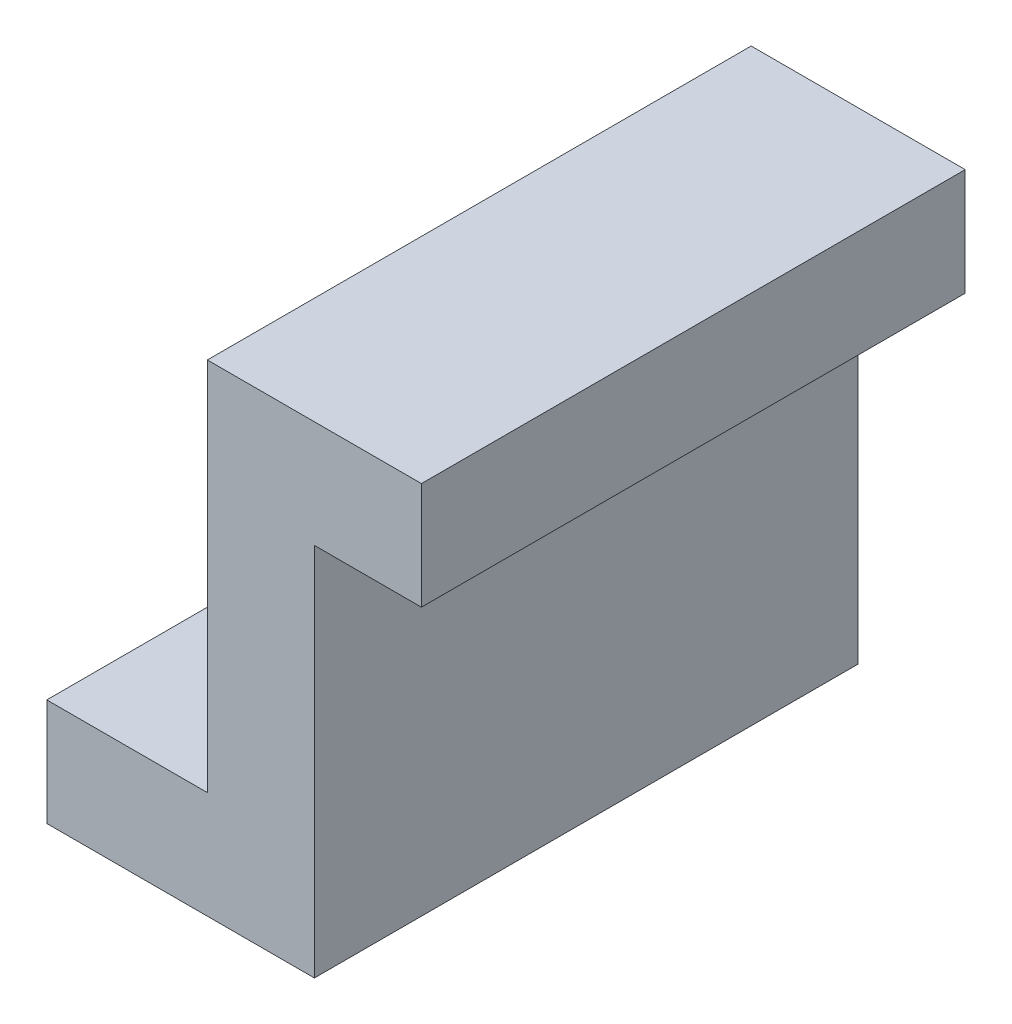
SolidWorks part; units mm, degrees
material "Aleación 6061"
ref_plane "Alzado" through (0, 0, 0) normal (0, 0, 1) x (1, 0, 0)
ref_plane "Planta" through (0, 0, 0) normal (0, 1, 0) x (1, 0, 0)
ref_plane "Vista lateral" through (0, 0, 0) normal (1, 0, 0) x (0, 0, -1)
sketch "Croquis1" plane through (0, 0, 0) normal (0, 0, 1) x (1, 0, 0)
  line L0 (0, 0) -> (25, 0)
  line L1 (25, 0) -> (25, 35)
  line L2 (25, 35) -> (35, 35)
  dimension "D1" = 35
  dimension "D2" = 25
  dimension "D3" = 10
extrude "Extruir-Lámina1" add sketch "Croquis1" along normal mid plane 50.8 thin thin type one direction reverse wall 10
sketch "Croquis2" plane through (0, 10, 0) normal (0, 1, 0) x (1, 0, 0)
  line L0 (7.5, 25.4) -> (7.5, -25.4) construction
  line L1 (0, 25.4) -> (15, 25.4) construction
  line L2 (0, -25.4) -> (15, -25.4) construction
  line L3 (0, 0) -> (15, 0) construction
  line L4 (15, -25.4) -> (15, 25.4) construction
  circle A0 centre (7.5, 0) radius 4.7625
  dimension "D1" = 9.525
extrude "Cortar-Extruir1" cut sketch "Croquis2" against normal through all
